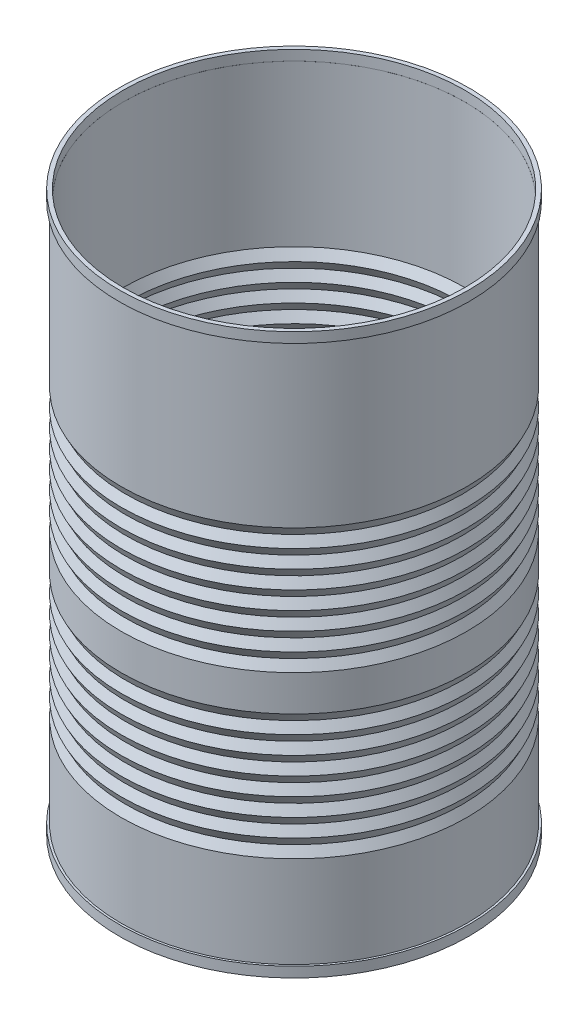
SolidWorks part; units mm, degrees
material "1023 Carbon Steel Sheet (SS)"
ref_plane "Front Plane" through (0, 0, 0) normal (0, 0, 1) x (1, 0, 0)
ref_plane "Top Plane" through (0, 0, 0) normal (0, 1, 0) x (1, 0, 0)
ref_plane "Right Plane" through (0, 0, 0) normal (1, 0, 0) x (0, 0, -1)
sketch "Sketch1" plane through (0, 0, 0) normal (0, 0, 1) x (1, 0, 0)
  line L0 (0, -1000) -> (0, 49000) construction
  line L1 (0, 0) -> (16.383, 0)
  line L2 (16.383, 0) -> (19.177, -0.635)
  line L3 (19.177, -0.635) -> (24.1935, -0.635)
  line L4 (52.6505, -0.635) -> (52.6505, -3.81)
  line L5 (52.6505, -3.81) -> (54.5886, -3.81)
  line L6 (54.5886, -3.81) -> (54.5886, -0.635)
  line L7 (54.5886, -0.635) -> (53.9425, -0.635)
  line L8 (53.9425, -0.635) -> (53.9425, 27.94)
  line L9 (53.9425, 167.64) -> (54.5886, 167.64)
  line L10 (54.5886, 167.64) -> (54.5886, 170.815)
  line L11 (54.5886, 170.815) -> (53.3186, 170.815)
  line L12 (53.9425, 27.94) -> (52.489, 30.734)
  line L13 (52.489, 30.734) -> (53.9425, 33.528)
  line L14 (53.9425, 67.056) -> (53.9425, 78.232)
  line L15 (52.489, 36.322) -> (53.9425, 39.116)
  line L16 (53.9425, 33.528) -> (52.489, 36.322)
  line L17 (52.489, 41.91) -> (53.9425, 44.704)
  line L18 (53.9425, 39.116) -> (52.489, 41.91)
  line L19 (52.489, 47.498) -> (53.9425, 50.292)
  line L20 (53.9425, 44.704) -> (52.489, 47.498)
  line L21 (52.489, 53.086) -> (53.9425, 55.88)
  line L22 (53.9425, 50.292) -> (52.489, 53.086)
  line L23 (52.489, 58.674) -> (53.9425, 61.468)
  line L24 (53.9425, 55.88) -> (52.489, 58.674)
  line L25 (52.489, 64.262) -> (53.9425, 67.056)
  line L26 (53.9425, 61.468) -> (52.489, 64.262)
  line L27 (52.489, 69.85) -> (53.9425, 72.644) [skipped]
  line L28 (53.9425, 67.056) -> (52.489, 69.85) [skipped]
  line L29 (52.489, 75.438) -> (53.9425, 78.232) [skipped]
  line L30 (53.9425, 72.644) -> (52.489, 75.438) [skipped]
  line L31 (52.489, 81.026) -> (53.9425, 83.82)
  line L32 (53.9425, 78.232) -> (52.489, 81.026)
  line L33 (52.489, 86.614) -> (53.9425, 89.408)
  line L34 (53.9425, 83.82) -> (52.489, 86.614)
  line L35 (52.489, 92.202) -> (53.9425, 94.996)
  line L36 (53.9425, 89.408) -> (52.489, 92.202)
  line L37 (52.489, 97.79) -> (53.9425, 100.584)
  line L38 (53.9425, 94.996) -> (52.489, 97.79)
  line L39 (52.489, 103.378) -> (53.9425, 106.172)
  line L40 (53.9425, 100.584) -> (52.489, 103.378)
  line L41 (52.489, 108.966) -> (53.9425, 111.76)
  line L42 (53.9425, 106.172) -> (52.489, 108.966)
  line L43 (52.489, 114.554) -> (53.9425, 117.348)
  line L44 (53.9425, 111.76) -> (52.489, 114.554)
  line L45 (53.9425, 117.348) -> (53.9425, 167.64)
  line L46 (53.3075, 0) -> (53.3075, 27.7847)
  line L47 (53.3075, 27.7847) -> (51.7732, 30.734)
  line L48 (51.7732, 30.734) -> (53.2268, 33.528)
  line L49 (53.2268, 33.528) -> (51.7732, 36.322)
  line L50 (51.7732, 36.322) -> (53.2268, 39.116)
  line L51 (53.2268, 39.116) -> (51.7732, 41.91)
  line L52 (51.7732, 41.91) -> (53.2268, 44.704)
  line L53 (53.2268, 44.704) -> (51.7732, 47.498)
  line L54 (51.7732, 47.498) -> (53.2268, 50.292)
  line L55 (53.2268, 50.292) -> (51.7732, 53.086)
  line L56 (51.7732, 53.086) -> (53.2268, 55.88)
  line L57 (53.2268, 55.88) -> (51.7732, 58.674)
  line L58 (51.7732, 58.674) -> (53.2268, 61.468)
  line L59 (53.2268, 61.468) -> (51.7732, 64.262)
  line L60 (51.7732, 64.262) -> (53.3075, 67.2113)
  line L61 (53.3075, 67.2113) -> (53.3075, 78.0767)
  line L62 (53.3075, 78.0767) -> (51.7732, 81.026)
  line L63 (51.7732, 81.026) -> (53.2268, 83.82)
  line L64 (53.2268, 83.82) -> (51.7732, 86.614)
  line L65 (51.7732, 86.614) -> (53.2268, 89.408)
  line L66 (53.2268, 89.408) -> (51.7732, 92.202)
  line L67 (51.7732, 92.202) -> (53.2268, 94.996)
  line L68 (53.2268, 94.996) -> (51.7732, 97.79)
  line L69 (51.7732, 97.79) -> (53.2268, 100.584)
  line L70 (53.2268, 100.584) -> (51.7732, 103.378)
  line L71 (51.7732, 103.378) -> (53.2268, 106.172)
  line L72 (53.2268, 106.172) -> (51.7732, 108.966)
  line L73 (51.7732, 108.966) -> (53.2268, 111.76)
  line L74 (53.2268, 111.76) -> (51.7732, 114.554)
  line L75 (51.7732, 114.554) -> (53.3075, 117.5033)
  line L76 (53.3075, 117.5033) -> (53.3075, 167.64)
  line L77 (0, 0.635) -> (16.4543, 0.635)
  line L78 (16.4543, 0.635) -> (19.2483, 0)
  line L79 (19.2483, 0) -> (24.4348, 0)
  line L80 (53.3075, 167.64) -> (53.3186, 167.64)
  line L81 (53.3186, 167.64) -> (53.3186, 170.815)
  line L82 (19.2483, 0) -> (52.6505, 0) construction
  line L83 (53.3075, -0.635) -> (53.3075, 27.7847) construction
  line L84 (0, 0.635) -> (0, 0)
  line L85 (29.5402, 0) -> (30.999, 0)
  line L86 (37.2, 0) -> (53.3075, 0)
  line L87 (37.4015, -0.635) -> (52.6505, -0.635)
  line L88 (19.177, -0.635) -> (52.6505, -0.635) construction
  line L89 (29.7815, -0.635) -> (30.7975, -0.635)
  arc A0 (24.1935, -0.635) -> (29.7815, -0.635) centre (26.9875, 2.6987) ccw
  arc A1 (30.7975, -0.635) -> (37.4015, -0.635) centre (34.0995, 4.2227) ccw
  arc A2 (24.4348, 0) -> (29.5402, 0) centre (26.9875, 2.6987) ccw
  arc A3 (30.999, 0) -> (37.2, 0) centre (34.0995, 4.2227) ccw
  arc A4 (24.6014, -0.1483) -> (29.3736, -0.1483) centre (26.9875, 2.6987) ccw construction
  arc A5 (31.1545, -0.1098) -> (37.0445, -0.1098) centre (34.0995, 4.2227) ccw construction
  point P91 (24.1935, -0.635)
  point P92 (29.7815, -0.635)
  point P93 (26.9875, -1.651)
  point P97 (34.0995, -1.651)
  point P98 (30.7975, -0.635)
  point P99 (37.4015, -0.635)
  dimension "D1" = 32.766
  dimension "D2" = 38.354
  dimension "D3" = 105.301
  dimension "D4" = 0.635
  dimension "D5" = 109.1771
  dimension "D6" = 3.175
  dimension "D7" = 3.175
  dimension "D8" = 107.8851
  dimension "D9" = 171.45
  dimension "D10" = 3.175
  dimension "D11" = 5.588
  dimension "D12" = 104.978
  dimension "D13" = 28.575
  dimension "D15" = 1.27
  dimension "D17" = 5.588
  dimension "D18" = 1.016
  dimension "D19" = 53.975
  dimension "D20" = 1.016
  dimension "D21" = 6.604
  dimension "D22" = 68.199
  dimension "D16" = 0.635
  dimension "D23" = 0.635
  dimension "D14" = 16
revolve "Revolve1" add sketch "Sketch1" angle 360 about L0
equation "\"scalefactor\" = 2.125 / 1.671"
